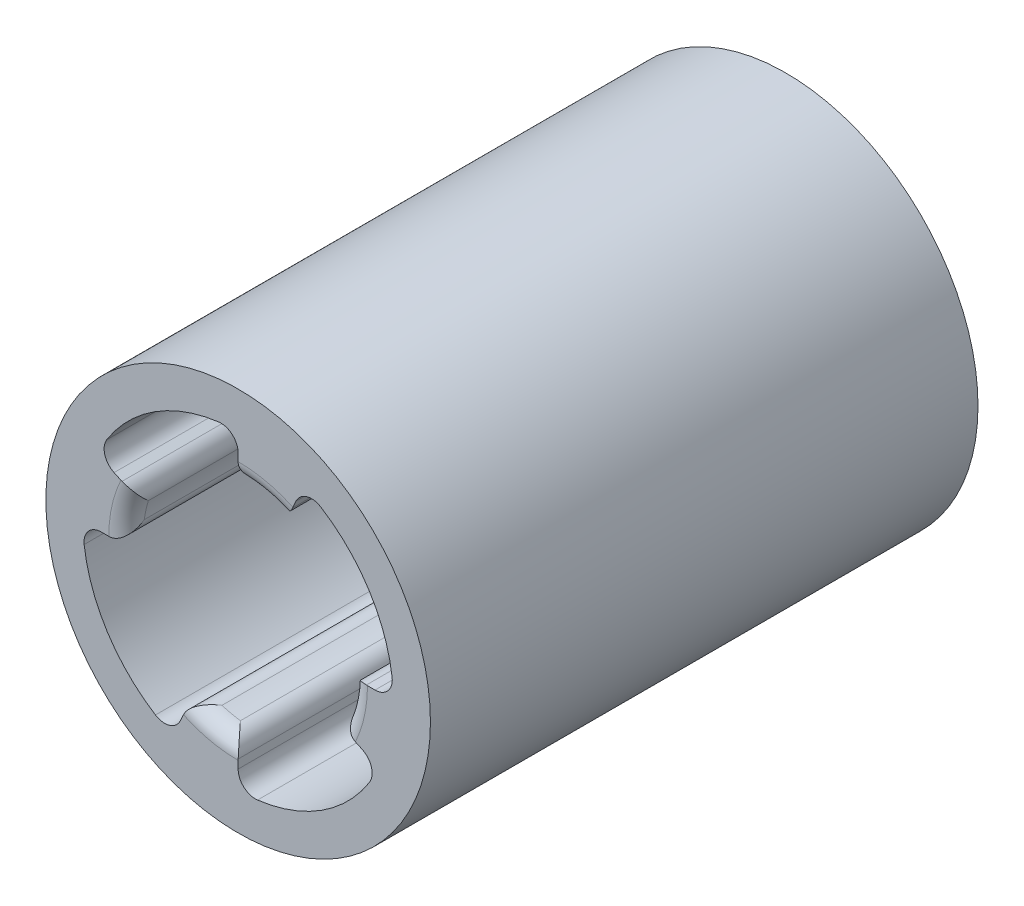
SolidWorks part; units mm, degrees
ref_plane "Front Plane" through (0, 0, 0) normal (0, 0, 1) x (1, 0, 0)
ref_plane "Top Plane" through (0, 0, 0) normal (0, 1, 0) x (1, 0, 0)
ref_plane "Right Plane" through (0, 0, 0) normal (1, 0, 0) x (0, 0, -1)
sketch "Sketch1" plane through (0, 0, 0) normal (0, 0, 1) x (1, 0, 0)
  circle A0 centre (0, 0) radius 11.15
  dimension "D1" = 22.3
extrude "Boss-Extrude1" add sketch "Sketch1" along normal blind 31.75
sketch "Sketch2" plane through (0, 0, 0) normal (0, 0, 1) x (1, 0, 0)
  line L0 (0, 6.5) -> (0, 9)
  line L2 (0, -9) -> (0, -6.5)
  line L3 (9, 0) -> (6.5, 0)
  line L4 (2.747, 5.891) -> (3.8036, 8.1568)
  line L5 (5.891, -2.747) -> (8.1568, -3.8036)
  line L6 (-2.747, -5.891) -> (-3.8036, -8.1568)
  line L7 (-5.891, 2.747) -> (-8.1568, 3.8036)
  line L8 (-6.5, 0) -> (-9, 0)
  arc A0 (-5.891, 2.747) -> (-6.5, 0) centre (0, 0) ccw
  arc A1 (-9, 0) -> (-3.8036, -8.1568) centre (0, 0) ccw
  arc A2 (2.747, 5.891) -> (0, 6.5) centre (0, 0) ccw
  arc A3 (5.891, -2.747) -> (6.5, 0) centre (0, 0) ccw
  arc A4 (-2.747, -5.891) -> (0, -6.5) centre (0, 0) ccw
  arc A5 (0, 9) -> (-8.1568, 3.8036) centre (0, 0) ccw
  arc A6 (9, 0) -> (3.8036, 8.1568) centre (0, 0) ccw
  arc A7 (0, -9) -> (8.1568, -3.8036) centre (0, 0) ccw
  dimension "D1" = 13
  dimension "D2" = 2.5
  dimension "D3" = 25
  dimension "D4" = 25
  dimension "D5" = 25
  dimension "D6" = 25
extrude "Cut-Extrude4" cut sketch "Sketch2" along normal through all
fillet "Fillet2" radius 1 16 edges at (-6.5, 0, 15.875) (-6.3459, 1.4069, 31.75) (-5.891, 2.747, 15.875) (-6.3459, 1.4069, 0) (0, -6.5, 15.875) (-1.4069, -6.3459, 31.75) (-2.747, -5.891, 15.875) (-1.4069, -6.3459, 0) (6.5, 0, 15.875) (6.3459, -1.4069, 31.75) (5.891, -2.747, 15.875) (6.3459, -1.4069, 0) (0, 6.5, 15.875) (1.4069, 6.3459, 31.75) (2.747, 5.891, 15.875) (1.4069, 6.3459, 0)
fillet "Fillet4" radius 1 8 edges at (0, 9, 15.875) (3.8036, 8.1568, 15.875) (9, 0, 15.875) (8.1568, -3.8036, 15.875) (0, -9, 15.875) (-3.8036, -8.1568, 15.875) (-9, 0, 15.875) (-8.1568, 3.8036, 15.875)
